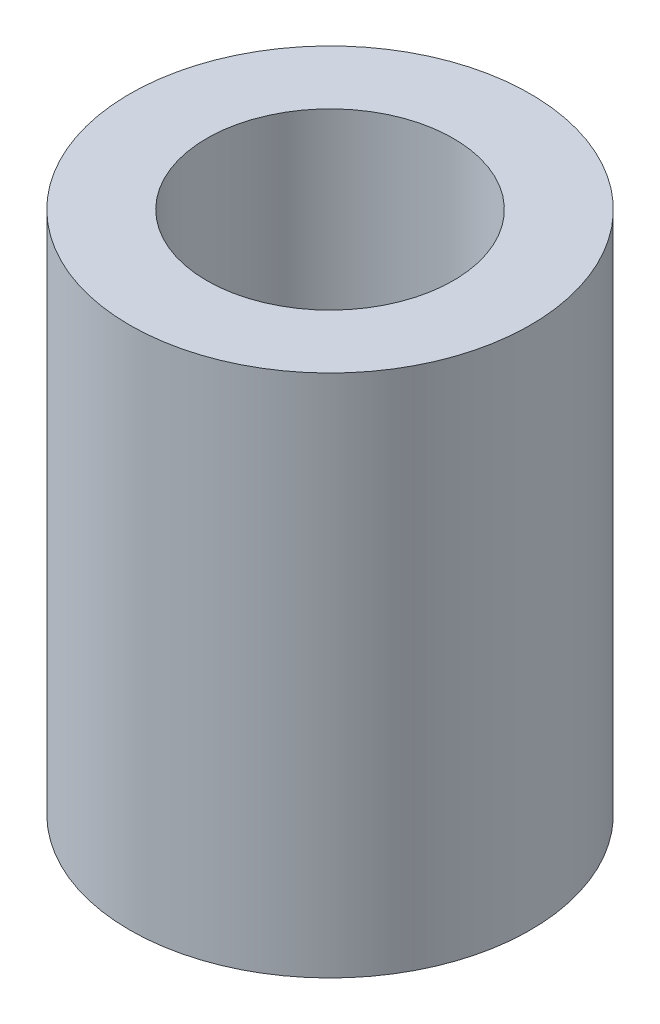
SolidWorks part; units mm, degrees
ref_plane "Front Plane" through (0, 0, 0) normal (0, 0, 1) x (1, 0, 0)
ref_plane "Top Plane" through (0, 0, 0) normal (0, 1, 0) x (1, 0, 0)
ref_plane "Right Plane" through (0, 0, 0) normal (1, 0, 0) x (0, 0, -1)
sketch "Sketch1" plane through (0, 0, 0) normal (0, 1, 0) x (1, 0, 0)
  circle A0 centre (0, 0) radius 6.5
  circle A1 centre (0, 0) radius 4
  dimension "D1" = 13
  dimension "D2" = 8
extrude "Boss-Extrude1" add sketch "Sketch1" along normal blind 17
